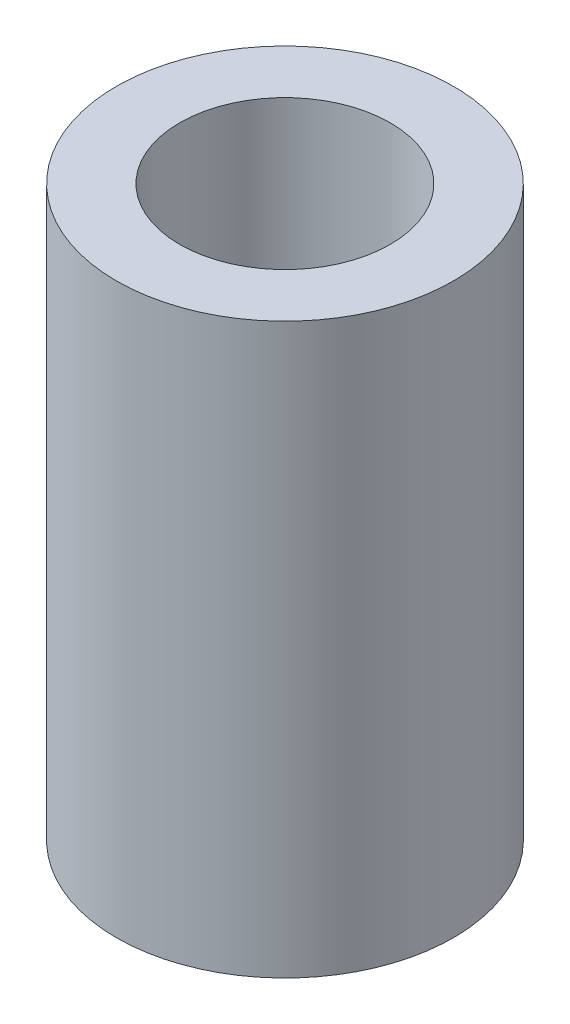
SolidWorks part; units mm, degrees
ref_plane "前视基准面" through (0, 0, 0) normal (0, 0, 1) x (1, 0, 0)
ref_plane "上视基准面" through (0, 0, 0) normal (0, 1, 0) x (1, 0, 0)
ref_plane "右视基准面" through (0, 0, 0) normal (1, 0, 0) x (0, 0, -1)
other "Configuration Table"
sketch "草图1" plane through (0, 0, 0) normal (0, 1, 0) x (1, 0, 0)
  circle A0 centre (0, 0) radius 2.5
  circle A1 centre (0, 0) radius 4
  dimension "D1" = 5
  dimension "D2" = 8
extrude "凸台-拉伸1" add sketch "草图1" along normal blind 13.5
